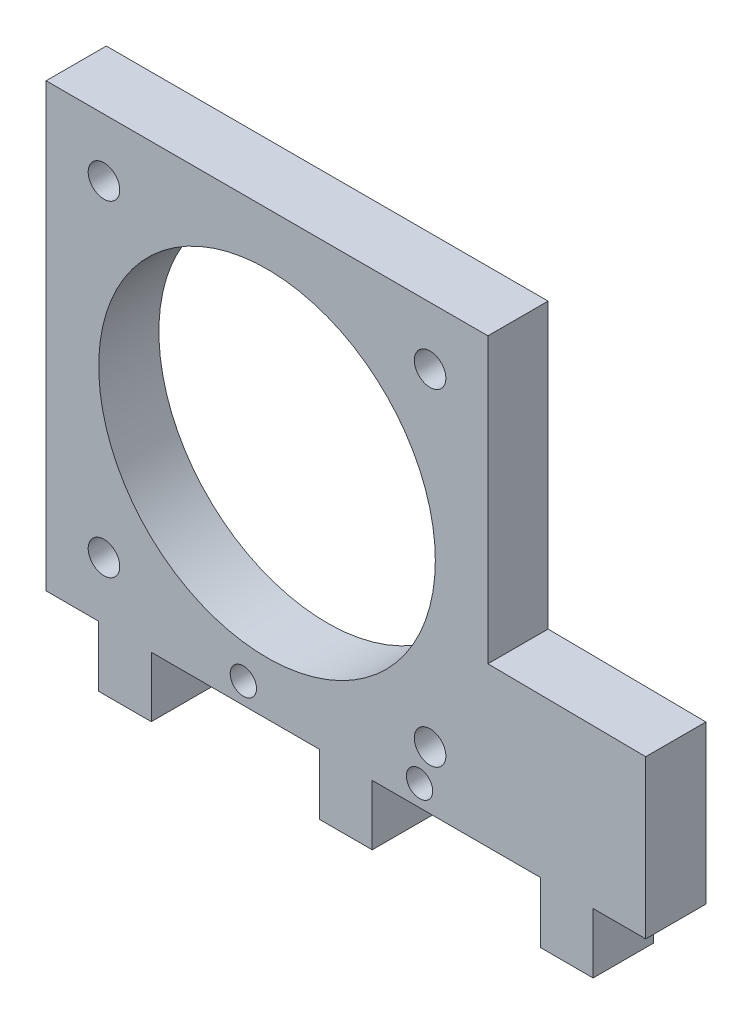
SolidWorks part; units mm, degrees
ref_plane "Front Plane" through (0, 0, 0) normal (0, 0, 1) x (1, 0, 0)
ref_plane "Top Plane" through (0, 0, 0) normal (0, 1, 0) x (1, 0, 0)
ref_plane "Right Plane" through (0, 0, 0) normal (1, 0, 0) x (0, 0, -1)
sketch "Sketch1" plane through (0, 0, 0) normal (0, 0, 1) x (1, 0, 0)
  line L0 (9.38, 32.1479) -> (9.38, 5.1479)
  line L1 (24.38, -10) -> (24.38, 5)
  line L2 (24.38, -10) -> (19.38, -10)
  line L3 (19.38, -10) -> (19.38, -15.72)
  line L4 (19.38, -15.72) -> (14.38, -15.72)
  line L5 (14.38, -15.72) -> (14.38, -9.9507)
  line L6 (14.38, -9.9507) -> (-1.62, -9.9507)
  line L7 (-1.62, -9.9507) -> (-1.62, -15.6707)
  line L8 (-1.62, -15.6707) -> (-6.62, -15.6707)
  line L9 (-6.62, -15.6707) -> (-6.62, -9.9014)
  line L10 (-6.62, -9.9014) -> (-22.62, -9.9014)
  line L11 (-22.62, -9.9014) -> (-22.62, -15.6214)
  line L12 (-22.62, -15.6214) -> (-27.62, -15.6214)
  line L13 (-27.62, -15.6214) -> (-27.62, -9.8521)
  line L14 (-27.62, -9.8521) -> (-32.62, -9.8521)
  line L15 (-32.62, -9.8521) -> (-32.62, 32.1479)
  line L16 (-32.62, 32.1479) -> (9.38, 32.1479)
  line L17 (9.38, 5.1479) -> (24.38, 5)
  circle A0 centre (-11.62, 11.1479) radius 16
  circle A1 centre (2.88, -7.9507) radius 1.25
  circle A2 centre (-13.87, -7.9014) radius 1.25
  circle A3 centre (3.8798, -4.4507) radius 1.5
  circle A4 centre (-27.12, -4.3521) radius 1.5
  circle A5 centre (-27.12, 26.6479) radius 1.5
  circle A6 centre (3.88, 26.6479) radius 1.5
  dimension "D17" = 32
  dimension "D18" = 21
  dimension "D19" = 3
  dimension "D20" = 2.5
  dimension "D21" = 2.5
  dimension "D23" = 2
  dimension "D24" = 4.5
  dimension "D25" = 7.25
  dimension "D14" = 15
  dimension "D26" = 3
  dimension "D27" = 3
  dimension "D28" = 3
  dimension "D29" = 5.5
  dimension "D30" = 21
  dimension "D31" = 5.5
  dimension "D32" = 5.5
  dimension "D33" = 5.5
  dimension "D35" = 5.5
  dimension "D36" = 5.5
  dimension "D3" = 5
  dimension "D4" = 16
  dimension "D5" = 16
  dimension "D6" = 5
  dimension "D7" = 5
  dimension "D8" = 5
  dimension "D9" = 5
  dimension "D10" = 5.72
  dimension "D11" = 5.72
  dimension "D12" = 5.72
  dimension "D13" = 42
  dimension "D15" = 42
  dimension "D16" = 27
  dimension "D22" = 2
  dimension "D34" = 31
extrude "Boss-Extrude1" add sketch "Sketch1" along normal blind 5.72
